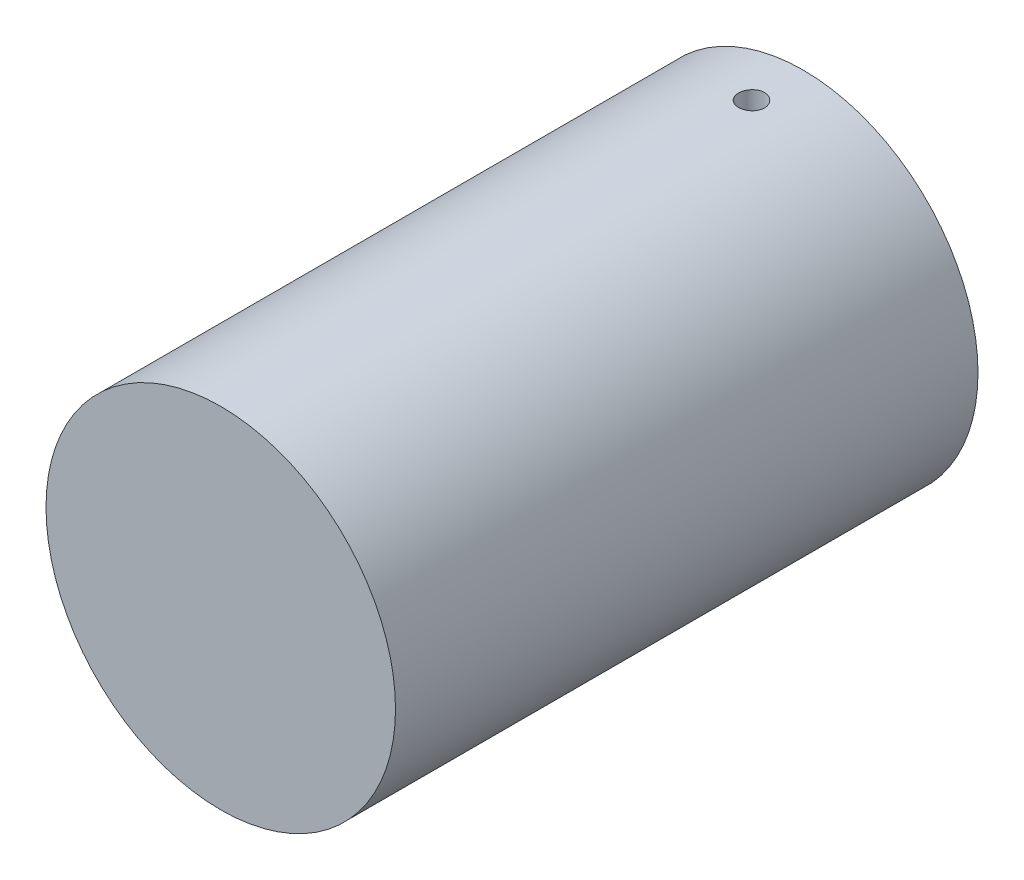
SolidWorks part; units mm, degrees
ref_plane "Front" through (0, 0, 0) normal (0, 0, 1) x (1, 0, 0)
ref_plane "Top" through (0, 0, 0) normal (0, 1, 0) x (1, 0, 0)
ref_plane "Right" through (0, 0, 0) normal (1, 0, 0) x (0, 0, -1)
sketch "Sketch1" plane through (0, 0, 0) normal (0, 0, 1) x (1, 0, 0)
  circle A0 centre (0, 0) radius 13.5
  dimension "D1" = 27
extrude "Boss-Extrude1" add sketch "Sketch1" along normal blind 45
sketch "Sketch2" plane through (0, 0, 0) normal (0, 1, 0) x (1, 0, 0)
  line L0 (0, 0) -> (0, -4) construction
  circle A0 centre (0, -4) radius 1
  dimension "D1" = 2
  dimension "D2" = 4
extrude "Cut-Extrude1" cut sketch "Sketch2" against normal through all both and the other way through all
